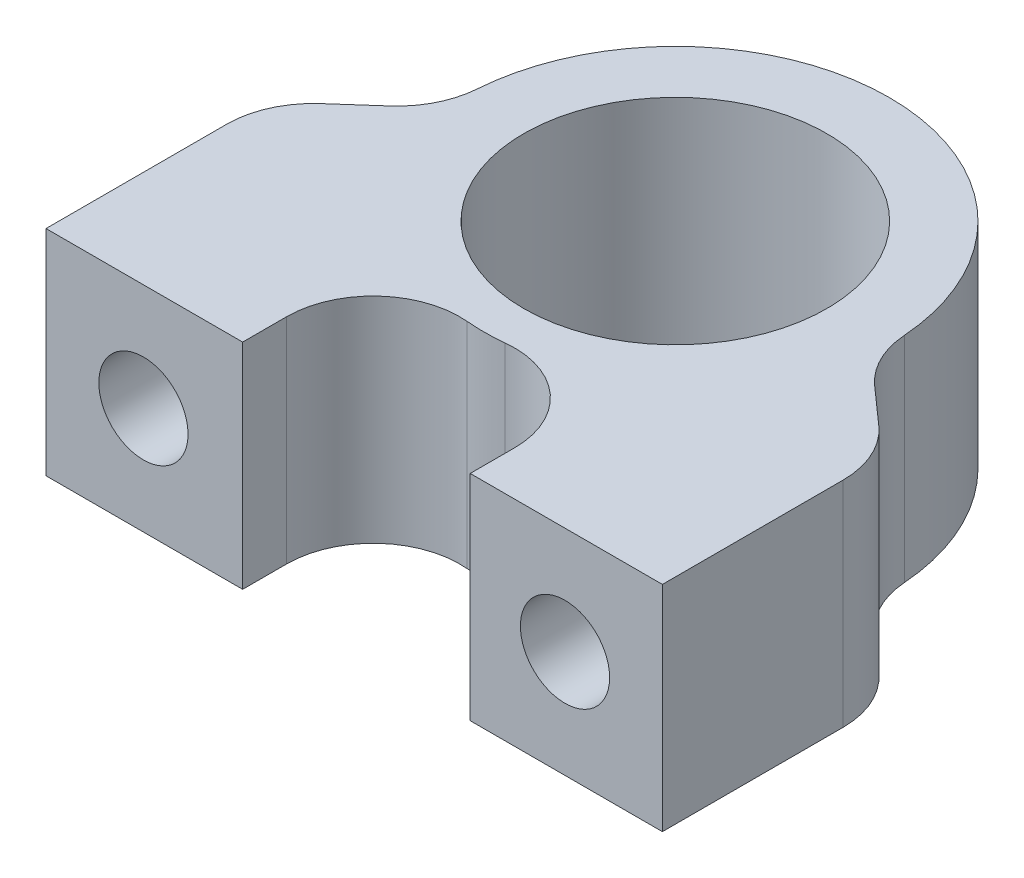
SolidWorks part; units mm, degrees
material "6061-T6 (SS)"
ref_plane "Front Plane" through (0, 0, 0) normal (0, 0, 1) x (1, 0, 0)
ref_plane "Top Plane" through (0, 0, 0) normal (0, 1, 0) x (1, 0, 0)
ref_plane "Right Plane" through (0, 0, 0) normal (1, 0, 0) x (0, 0, -1)
sketch "Sketch1" plane through (0, 0, 0) normal (0, 1, 0) x (1, 0, 0)
  line L5 (-8, -17.9935) -> (0, -11.9935) construction
  line L6 (-13.2136, -2.0833) -> (0, -11.9935) construction
  line L7 (-11.9935, 0) -> (-11.9935, -1)
  line L8 (-14.75, -7.2935) -> (-8.75, -7.2935) construction
  line L9 (-8.75, -7.2935) -> (-8.75, -11.2935) construction
  line L10 (-8.75, -11.2935) -> (-8.75, -17.9935) construction
  line L11 (-11.9935, -1) -> (-17.2701, -5.6848)
  line L12 (-16, -17.9935) -> (16, -17.9935)
  line L13 (0, -17.9935) -> (0, 17.0541) construction
  line L14 (14.75, -7.2935) -> (14.75, -17.9935) construction
  line L15 (-14.75, -7.2935) -> (-14.75, -17.9935) construction
  line L17 (-17.2701, -5.6848) -> (-17.2701, -17.9935)
  line L18 (-17.2701, -17.9935) -> (-16, -17.9935)
  line L19 (8.75, -11.2935) -> (8.75, -17.9935) construction
  line L20 (8.75, -7.2935) -> (8.75, -11.2935) construction
  line L21 (14.75, -7.2935) -> (8.75, -7.2935) construction
  line L22 (13.2136, -2.0833) -> (0, -11.9935) construction
  line L23 (8, -17.9935) -> (0, -11.9935) construction
  line L24 (17.2701, -17.9935) -> (16, -17.9935)
  line L25 (17.2701, -5.6848) -> (17.2701, -17.9935)
  line L26 (11.9935, -1) -> (17.2701, -5.6848)
  line L27 (11.9935, 0) -> (11.9935, -1)
  circle A0 centre (0, 0) radius 8.4935
  arc A1 (11.9935, 0) -> (-11.9935, 0) centre (0, 0) ccw
  circle A3 centre (0, 0) radius 11.9935 construction
  circle A4 centre (0, 0) radius 8.4935 construction
  point P5 (0, -11.9935)
  dimension "D1" = 16.987
  dimension "D2" = 3.5
extrude "Boss-Extrude1" add sketch "Sketch1" along normal blind 12
sketch "Sketch2" plane through (0, 0, 17.9935) normal (0, 0, 1) x (1, 0, 0)
  line L0 (-17.2701, 12) -> (-11.8114, 12) construction
  line L1 (-17.2701, 12) -> (17.2701, 12) construction
  line L2 (-11.8114, 12) -> (-11.8114, 6) construction
  line L3 (17.2701, 12) -> (11.8114, 12) construction
  line L4 (11.8114, 12) -> (11.8114, 6) construction
  circle A0 centre (-11.8114, 6) radius 2.5
  circle A1 centre (11.8114, 6) radius 2.5
extrude "Cut-Extrude1" cut sketch "Sketch2" against normal blind 10.5
sketch "Sketch3" plane through (0, 12, 0) normal (0, 1, 0) x (1, 0, 0)
  line L0 (-9.3114, -17.9935) -> (-6.25, -17.9935) construction
  line L1 (-17.2701, -17.9935) -> (17.2701, -17.9935) construction
  line L2 (-6.25, -17.9935) -> (-6.25, -8.7384)
  line L3 (9.3114, -17.9935) -> (6.5, -17.9935) construction
  line L4 (6.5, -17.9935) -> (6.5, -8.5541)
  line L5 (-6.25, -17.9935) -> (6.5, -17.9935)
  circle A3 centre (0, 0) radius 10.7435
  arc A4 (-6.25, -8.7384) -> (6.5, -8.5541) centre (0, 0) ccw
  dimension "D1" = 2.25
extrude "Cut-Extrude2" cut sketch "Sketch3" against normal blind 20
fillet "Fillet1" radius 4.85 6 edges at (6.5, 6, 8.5541) (-6.25, 6, 8.7384) (-17.2701, 6, 5.6848) (-11.9935, 6, 1) (11.9935, 6, 1) (17.2701, 6, 5.6848)
